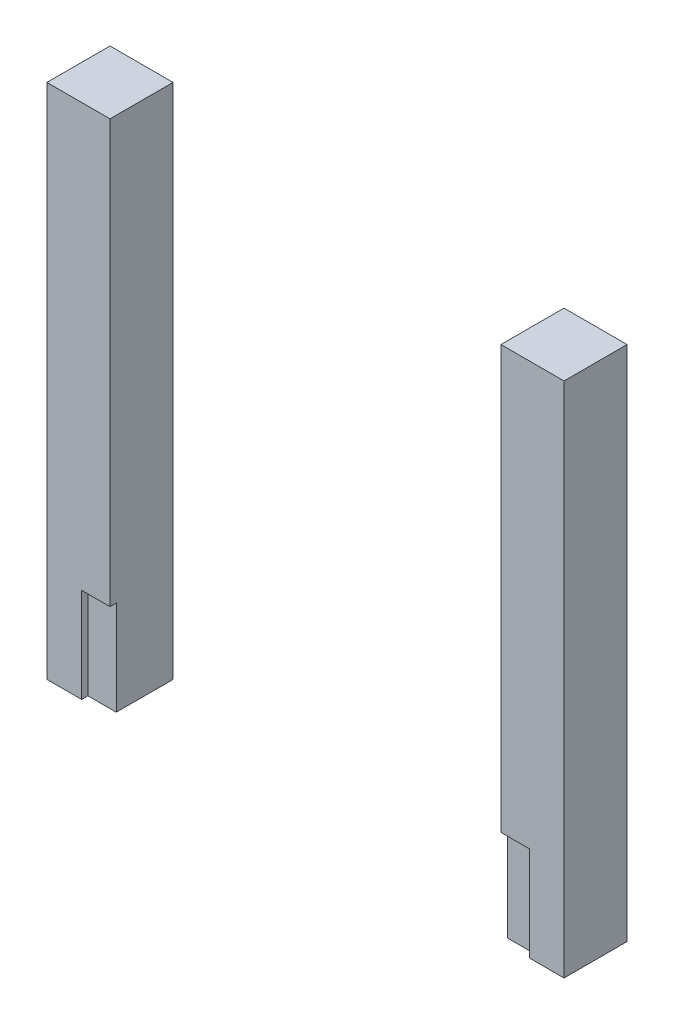
SolidWorks part; units mm, degrees
ref_plane "Front Plane" through (0, 0, 0) normal (0, 0, 1) x (1, 0, 0)
ref_plane "Top Plane" through (0, 0, 0) normal (0, 1, 0) x (1, 0, 0)
ref_plane "Right Plane" through (0, 0, 0) normal (1, 0, 0) x (0, 0, -1)
sketch "Sketch1" plane through (0, 0, 0) normal (0, 0, 1) x (1, 0, 0)
  line L1 (-310, 310) -> (310, 310)
  line L2 (-310, 310) -> (-310, -310)
  line L3 (-310, -310) -> (310, -310)
  line L4 (310, 310) -> (310, -310)
  line L5 (-310, 310) -> (310, -310) construction
  line L6 (-310, -310) -> (310, 310) construction
  line L7 (-410, 410) -> (410, 410)
  line L8 (-410, 410) -> (-410, -410)
  line L9 (-410, -410) -> (410, -410)
  line L10 (410, 410) -> (410, -410)
  line L11 (-410, 410) -> (410, -410) construction
  line L12 (-410, -410) -> (410, 410) construction
  point P0 (0, 0)
  point P6 (0, 0)
  dimension "D1" = 620
  dimension "D2" = 820
extrude "Boss-Extrude1" add sketch "Sketch1" along normal mid plane 100
sketch "Sketch2" plane through (0, 0, 50) normal (0, 0, 1) x (1, 0, 0)
  line L0 (-410, -410) -> (410, -410) construction
  line L1 (-355, -260) -> (355, -260)
  line L2 (-355, -260) -> (-355, -410)
  line L3 (-355, -410) -> (355, -410)
  line L4 (355, -260) -> (355, -410)
  line L5 (-355, -260) -> (355, -410) construction
  line L6 (-355, -410) -> (355, -260) construction
  point P0 (0, -335)
  dimension "D1" = 710
  dimension "D2" = 150
extrude "Cut-Extrude1" cut sketch "Sketch2" against normal blind 10
sketch "Sketch3" plane through (0, 0, -50) normal (0, 0, -1) x (-1, 0, 0)
  line L6 (-310, -310) -> (310, -310)
  line L7 (310, 310) -> (310, 410)
  line L8 (-410, 410) -> (410, 410) construction
  line L9 (310, 410) -> (-310, 410)
  line L10 (-310, 410) -> (-310, 310)
  line L11 (-310, 310) -> (310, 310)
  line L12 (-310, -310) -> (-310, -410)
  line L13 (410, -410) -> (-410, -410) construction
  line L14 (-310, -410) -> (310, -410)
  line L15 (310, -410) -> (310, -310)
extrude "Cut-Extrude2" cut sketch "Sketch3" against normal through all
